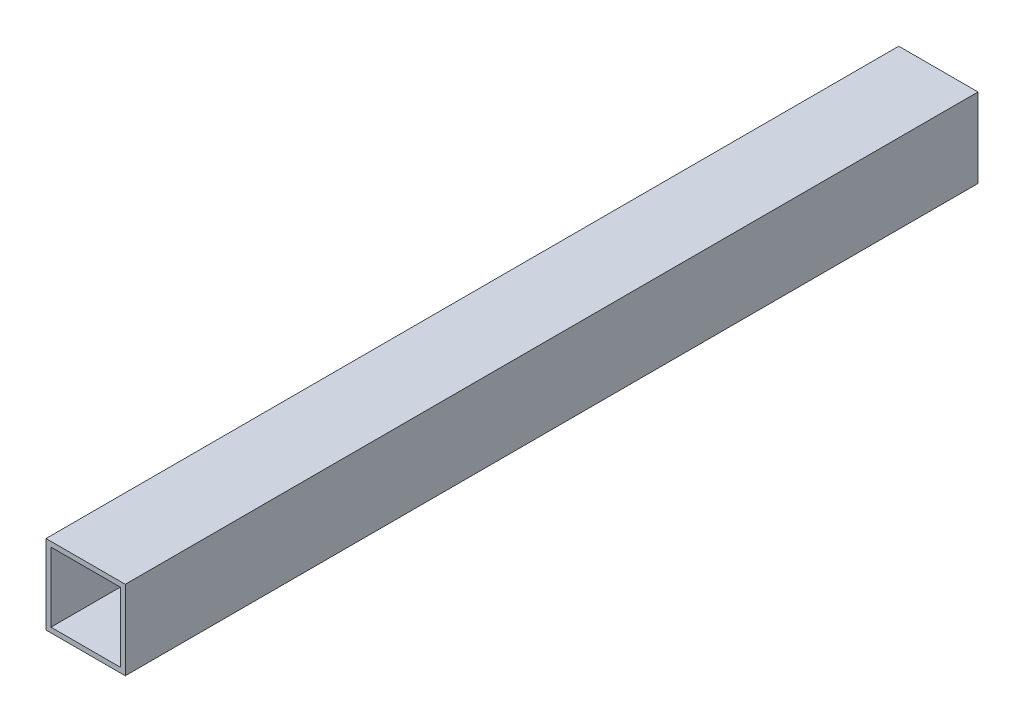
SolidWorks part; units mm, degrees
ref_plane "Front Plane" through (0, 0, 0) normal (0, 0, 1) x (1, 0, 0)
ref_plane "Top Plane" through (0, 0, 0) normal (0, 1, 0) x (1, 0, 0)
ref_plane "Right Plane" through (0, 0, 0) normal (1, 0, 0) x (0, 0, -1)
sketch "Sketch1" plane through (0, 0, 0) normal (0, 0, 1) x (1, 0, 0)
  line L1 (-18.2557, 23.6578) -> (32.5443, 23.6578)
  line L2 (-18.2557, 23.6578) -> (-18.2557, -27.1422)
  line L3 (-18.2557, -27.1422) -> (32.5443, -27.1422)
  line L4 (32.5443, 23.6578) -> (32.5443, -27.1422)
  line L5 (-15.0807, 20.4828) -> (29.3693, 20.4828)
  line L6 (-15.0807, 20.4828) -> (-15.0807, -23.9672)
  line L7 (-15.0807, -23.9672) -> (29.3693, -23.9672)
  line L8 (29.3693, 20.4828) -> (29.3693, -23.9672)
  dimension "D1" = 3.175
  dimension "D2" = 3.175
  dimension "D3" = 3.175
  dimension "D4" = 3.175
  dimension "D5" = 50.8
extrude "Boss-Extrude2" add sketch "Sketch1" along normal blind 546.5345
equation "\"D2@Sketch1\"= \"D1@Sketch1\""
equation "\"D3@Sketch1\"= \"D1@Sketch1\""
equation "\"D4@Sketch1\"= \"D1@Sketch1\""
